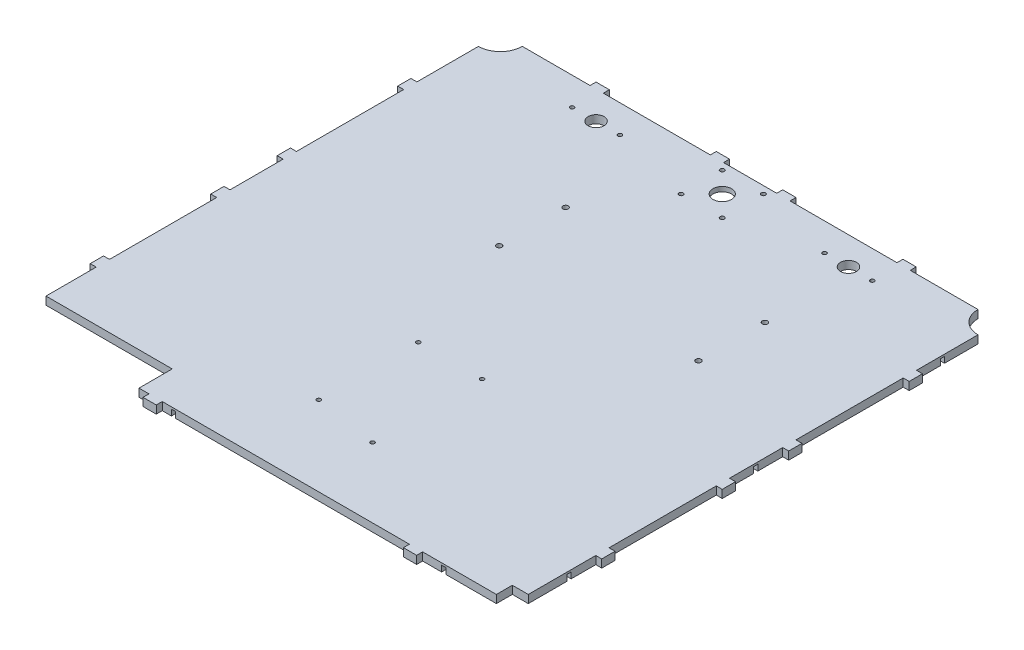
SolidWorks part; units mm, degrees
ref_plane "Alzado" through (0, 0, 0) normal (0, 0, 1) x (1, 0, 0)
ref_plane "Planta" through (0, 0, 0) normal (0, 1, 0) x (1, 0, 0)
ref_plane "Vista lateral" through (0, 0, 0) normal (1, 0, 0) x (0, 0, -1)
sketch "Croquis1" plane through (0, 0, 0) normal (0, 1, 0) x (1, 0, 0)
  line L0 (0, 0) -> (67.5, 0)
  line L1 (188, 367) -> (188, 375.2829) construction
  line L4 (77.5, 0) -> (102.5, 0)
  line L5 (0, 0) -> (0, 62.8)
  line L6 (0, 62.8) -> (-4.5, 62.8)
  line L7 (-4.5, 62.8) -> (-4.5, 72.8)
  line L8 (-4.5, 72.8) -> (0, 72.8)
  line L9 (0, 72.8) -> (0, 153.5)
  line L10 (0, 153.5) -> (-4.5, 153.5)
  line L11 (-4.5, 153.5) -> (-4.5, 163.5)
  line L12 (-4.5, 163.5) -> (0, 163.5)
  line L13 (0, 163.5) -> (0, 203.5)
  line L14 (0, 183.5) -> (180.5, 183.5) construction
  line L15 (188, 367) -> (188, 0) construction
  line L16 (-4.5, 203.5) -> (0, 203.5)
  line L17 (-4.5, 213.5) -> (-4.5, 203.5)
  line L18 (0, 213.5) -> (-4.5, 213.5)
  line L19 (0, 294.2) -> (0, 213.5)
  line L20 (-4.5, 294.2) -> (0, 294.2)
  line L21 (-4.5, 304.2) -> (-4.5, 294.2)
  line L22 (0, 304.2) -> (-4.5, 304.2)
  line L23 (0, 304.2) -> (0, 350.5)
  line L24 (16.5, 367) -> (67.5, 367)
  line L25 (67.5, 367) -> (67.5, 371.5)
  line L26 (67.5, 371.5) -> (77.5, 371.5)
  line L27 (77.5, 371.5) -> (77.5, 367)
  line L28 (77.5, 367) -> (158, 367)
  line L29 (158, 367) -> (158, 371.5)
  line L30 (158, 371.5) -> (168, 371.5)
  line L31 (168, 371.5) -> (168, 367)
  line L32 (168, 367) -> (208, 367)
  line L33 (376, 163.5) -> (376, 203.5)
  line L34 (380.5, 163.5) -> (376, 163.5)
  line L35 (380.5, 153.5) -> (380.5, 163.5)
  line L36 (376, 153.5) -> (380.5, 153.5)
  line L37 (376, 72.8) -> (376, 153.5)
  line L38 (380.5, 72.8) -> (376, 72.8)
  line L39 (380.5, 62.8) -> (380.5, 72.8)
  line L40 (376, 62.8) -> (380.5, 62.8)
  line L41 (376, 0) -> (376, 62.8)
  line L42 (298.5, -4.5) -> (298.5, 0)
  line L43 (308.5, -4.5) -> (298.5, -4.5)
  line L44 (308.5, 0) -> (308.5, -4.5)
  line L45 (376, 0) -> (308.5, 0)
  line L46 (208, 371.5) -> (208, 367)
  line L47 (218, 371.5) -> (208, 371.5)
  line L48 (218, 367) -> (218, 371.5)
  line L49 (298.5, 367) -> (218, 367)
  line L50 (298.5, 371.5) -> (298.5, 367)
  line L51 (308.5, 371.5) -> (298.5, 371.5)
  line L52 (308.5, 367) -> (308.5, 371.5)
  line L53 (359.5, 367) -> (308.5, 367)
  line L54 (376, 350.5) -> (376, 304.2)
  line L55 (376, 304.2) -> (380.5, 304.2)
  line L56 (380.5, 304.2) -> (380.5, 294.2)
  line L57 (380.5, 294.2) -> (376, 294.2)
  line L58 (376, 294.2) -> (376, 213.5)
  line L59 (376, 213.5) -> (380.5, 213.5)
  line L60 (380.5, 213.5) -> (380.5, 203.5)
  line L61 (380.5, 203.5) -> (376, 203.5)
  line L62 (102.5, 0) -> (102.5, 14.5062) construction
  line L63 (112.5, 0) -> (298.5, 0)
  line L64 (67.5, 0) -> (77.5, 0)
  line L65 (102.5, 0) -> (102.5, -4.5)
  line L66 (102.5, -4.5) -> (112.5, -4.5)
  line L67 (112.5, 0) -> (112.5, -4.5)
  arc A0 (0, 350.5) -> (16.5, 367) centre (0, 367) ccw
  arc A1 (376, 350.5) -> (359.5, 367) centre (376, 367) cw
  dimension "D8" = 33
  dimension "D14" = 46.3
  dimension "D2" = 20
  dimension "D5" = 62.8
  dimension "D6" = 4.5
  dimension "D7" = 10
  dimension "D9" = 10
  dimension "D10" = 20
  dimension "D11" = 51
  dimension "D12" = 10
  dimension "D13" = 4.5
  dimension "D15" = 10
  dimension "D16" = 16.5
  dimension "D17" = 16.5
  dimension "D18" = 25
  dimension "D19" = 10
extrude "Saliente-Extruir1" add sketch "Croquis1" against normal blind 6
sketch "Croquis3" plane through (0, -6, 0) normal (0, -1, 0) x (1, 0, 0)
  line L0 (324.3519, 0) -> (324.3519, -11.6932) construction
  line L1 (325.9019, -6.5002) -> (325.9019, 0)
  line L2 (327.1922, -8.0283) -> (327.1922, -9.5783)
  line L3 (322.2204, -10.8802) -> (322.3896, -10.8802)
  line L4 (325.9019, 0) -> (322.8019, 0)
  line L5 (321.5115, -8.0283) -> (321.5115, -9.5783)
  line L6 (326.4834, -10.8802) -> (326.3141, -10.8802)
  line L7 (322.8019, -6.5002) -> (322.8019, 0)
  line L8 (0, -323.9093) -> (6.5002, -323.9093) construction
  line L9 (324.3519, -11.6932) -> (324.3519, 0.5178) construction
  line L10 (188, 0) -> (188, -367) construction
  line L11 (324.3519, -367) -> (324.3519, -355.3068) construction
  line L12 (208, -367) -> (168, -367) construction
  line L13 (322.8019, -360.4998) -> (322.8019, -367)
  line L14 (8.0283, -326.7496) -> (9.5783, -326.7496)
  line L15 (10.8802, -321.7778) -> (10.8802, -321.947)
  line L16 (6.5002, -322.3593) -> (0, -322.3593)
  line L17 (6.5002, -325.4593) -> (0, -325.4593)
  line L18 (10.8802, -326.0408) -> (10.8802, -325.8715)
  line L19 (0, -323.9093) -> (11.6932, -323.9093) construction
  line L20 (321.5115, -358.9717) -> (321.5115, -357.4217)
  line L21 (0, -322.3593) -> (0, -325.4593)
  line L22 (0, -42.91) -> (11.6932, -42.91) construction
  line L23 (6.5002, -41.36) -> (0, -41.36)
  line L24 (10.8802, -45.0415) -> (10.8802, -44.8722)
  line L25 (8.0283, -40.0697) -> (9.5783, -40.0697)
  line L26 (0, -44.46) -> (0, -41.36)
  line L27 (10.8802, -40.7785) -> (10.8802, -40.9478)
  line L28 (8.0283, -45.7503) -> (9.5783, -45.7503)
  line L29 (6.5002, -44.46) -> (0, -44.46)
  line L30 (326.4834, -356.1198) -> (326.3141, -356.1198)
  line L31 (8.0283, -321.0689) -> (9.5783, -321.0689)
  line L32 (121.0007, 0) -> (121.0007, -11.6932) construction
  line L33 (0, -183.2411) -> (376, -183.2411) construction
  line L34 (322.8019, -367) -> (325.9019, -367)
  line L35 (327.1922, -358.9717) -> (327.1922, -357.4217)
  line L36 (8.0283, -186.246) -> (9.5783, -186.246)
  line L37 (10.8802, -181.2741) -> (10.8802, -181.4434)
  line L38 (6.5002, -181.8556) -> (0, -181.8556)
  line L39 (6.5002, -184.9556) -> (0, -184.9556)
  line L40 (10.8802, -185.5371) -> (10.8802, -185.3679)
  line L41 (0, -183.4056) -> (11.6932, -183.4056) construction
  line L42 (0, -181.8556) -> (0, -184.9556)
  line L43 (8.0283, -180.5653) -> (9.5783, -180.5653)
  line L44 (122.5507, -6.5002) -> (122.5507, 0)
  line L45 (123.841, -8.0283) -> (123.841, -9.5783)
  line L46 (118.8692, -10.8802) -> (119.0384, -10.8802)
  line L47 (122.5507, 0) -> (119.4507, 0)
  line L48 (118.1603, -8.0283) -> (118.1603, -9.5783)
  line L49 (123.1322, -10.8802) -> (122.9629, -10.8802)
  line L50 (376, -42.7364) -> (364.3068, -42.7364) construction
  line L51 (369.4998, -44.2864) -> (376, -44.2864)
  line L52 (367.9717, -45.5768) -> (366.4217, -45.5768)
  line L53 (365.1198, -40.6049) -> (365.1198, -40.7742)
  line L54 (376, -44.2864) -> (376, -41.1864)
  line L55 (367.9717, -39.8961) -> (366.4217, -39.8961)
  line L56 (365.1198, -44.8679) -> (365.1198, -44.6987)
  line L57 (369.4998, -41.1864) -> (376, -41.1864)
  line L58 (376, -183.2411) -> (364.3068, -183.2411) construction
  line L59 (367.9717, -180.4008) -> (366.4217, -180.4008)
  line L60 (376, -181.6911) -> (376, -184.7911)
  line L61 (365.1198, -185.3726) -> (365.1198, -185.2033)
  line L62 (369.4998, -184.7911) -> (376, -184.7911)
  line L63 (369.4998, -181.6911) -> (376, -181.6911)
  line L64 (365.1198, -181.1096) -> (365.1198, -181.2788)
  line L65 (367.9717, -186.0814) -> (366.4217, -186.0814)
  line L66 (376, -323.728) -> (364.3068, -323.728) construction
  line L67 (369.4998, -325.278) -> (376, -325.278)
  line L68 (365.1198, -321.5965) -> (365.1198, -321.7657)
  line L69 (367.9717, -326.5683) -> (366.4217, -326.5683)
  line L70 (376, -322.178) -> (376, -325.278)
  line L71 (365.1198, -325.8594) -> (365.1198, -325.6902)
  line L72 (367.9717, -320.8876) -> (366.4217, -320.8876)
  line L73 (369.4998, -322.178) -> (376, -322.178)
  line L74 (324.3519, -355.9508) -> (324.3519, -367) construction
  line L75 (51.6481, -367) -> (51.6481, -355.3068) construction
  line L76 (50.0981, -360.4998) -> (50.0981, -367)
  line L77 (48.8078, -358.9717) -> (48.8078, -357.4217)
  line L78 (53.7796, -356.1198) -> (53.6104, -356.1198)
  line L79 (50.0981, -367) -> (53.1981, -367)
  line L80 (54.4885, -358.9717) -> (54.4885, -357.4217)
  line L81 (51.6481, -355.9508) -> (51.6481, -367) construction
  line L82 (51.6481, 0.5178) -> (51.6481, -24.8622) construction
  line L83 (322.2204, -356.1198) -> (322.3896, -356.1198)
  line L84 (119.4507, -6.5002) -> (119.4507, 0)
  line L85 (121.0007, -11.6932) -> (121.0007, 0) construction
  line L86 (325.9019, -360.4998) -> (325.9019, -367)
  line L87 (324.3519, -355.3068) -> (324.3519, -367.5178) construction
  line L88 (49.5166, -356.1198) -> (49.6859, -356.1198)
  line L89 (53.1981, -360.4998) -> (53.1981, -367)
  line L90 (51.6481, -355.3068) -> (51.6481, -367.5178) construction
  line L96 (51.6481, -355.9508) -> (51.6481, -367) construction
  arc A0 (327.1922, -8.0283) -> (325.9019, -6.5002) centre (325.6422, -8.0283) ccw
  arc A1 (322.3896, -10.8802) -> (326.3141, -10.8802) centre (324.3519, -8.9187) ccw
  arc A2 (322.2204, -10.8802) -> (321.5115, -9.5783) centre (323.0615, -9.5783) cw
  arc A3 (326.4834, -10.8802) -> (327.1922, -9.5783) centre (325.6422, -9.5783) ccw
  arc A4 (321.5115, -8.0283) -> (322.8019, -6.5002) centre (323.0615, -8.0283) cw
  arc A5 (8.0283, -321.0689) -> (6.5002, -322.3593) centre (8.0283, -322.6189) ccw
  arc A6 (8.0283, -326.7496) -> (6.5002, -325.4593) centre (8.0283, -325.1996) cw
  arc A7 (10.8802, -326.0408) -> (9.5783, -326.7496) centre (9.5783, -325.1996) cw
  arc A8 (10.8802, -321.7778) -> (9.5783, -321.0689) centre (9.5783, -322.6189) ccw
  arc A9 (10.8802, -325.8715) -> (10.8802, -321.947) centre (8.9187, -323.9093) ccw
  arc A10 (8.0283, -40.0697) -> (6.5002, -41.36) centre (8.0283, -41.6197) ccw
  arc A11 (10.8802, -45.0415) -> (9.5783, -45.7503) centre (9.5783, -44.2003) cw
  arc A12 (10.8802, -40.7785) -> (9.5783, -40.0697) centre (9.5783, -41.6197) ccw
  arc A13 (10.8802, -40.9478) -> (10.8802, -44.8722) centre (8.9187, -42.91) cw
  arc A14 (8.0283, -45.7503) -> (6.5002, -44.46) centre (8.0283, -44.2003) cw
  arc A15 (8.0283, -180.5653) -> (6.5002, -181.8556) centre (8.0283, -182.1153) ccw
  arc A16 (8.0283, -186.246) -> (6.5002, -184.9556) centre (8.0283, -184.696) cw
  arc A17 (10.8802, -185.5371) -> (9.5783, -186.246) centre (9.5783, -184.696) cw
  arc A18 (10.8802, -181.2741) -> (9.5783, -180.5653) centre (9.5783, -182.1153) ccw
  arc A19 (10.8802, -185.3679) -> (10.8802, -181.4434) centre (8.9187, -183.4056) ccw
  arc A20 (123.841, -8.0283) -> (122.5507, -6.5002) centre (122.291, -8.0283) ccw
  arc A21 (119.0384, -10.8802) -> (122.9629, -10.8802) centre (121.0007, -8.9187) ccw
  arc A22 (118.8692, -10.8802) -> (118.1603, -9.5783) centre (119.7103, -9.5783) cw
  arc A23 (123.1322, -10.8802) -> (123.841, -9.5783) centre (122.291, -9.5783) ccw
  arc A24 (118.1603, -8.0283) -> (119.4507, -6.5002) centre (119.7103, -8.0283) cw
  arc A25 (367.9717, -45.5768) -> (369.4998, -44.2864) centre (367.9717, -44.0268) ccw
  arc A26 (365.1198, -40.7742) -> (365.1198, -44.6987) centre (367.0813, -42.7364) ccw
  arc A27 (365.1198, -40.6049) -> (366.4217, -39.8961) centre (366.4217, -41.4461) cw
  arc A28 (365.1198, -44.8679) -> (366.4217, -45.5768) centre (366.4217, -44.0268) ccw
  arc A29 (367.9717, -39.8961) -> (369.4998, -41.1864) centre (367.9717, -41.4461) cw
  arc A30 (365.1198, -185.2033) -> (365.1198, -181.2788) centre (367.0813, -183.2411) cw
  arc A31 (365.1198, -181.1096) -> (366.4217, -180.4008) centre (366.4217, -181.9508) cw
  arc A32 (365.1198, -185.3726) -> (366.4217, -186.0814) centre (366.4217, -184.5314) ccw
  arc A33 (367.9717, -186.0814) -> (369.4998, -184.7911) centre (367.9717, -184.5314) ccw
  arc A34 (367.9717, -180.4008) -> (369.4998, -181.6911) centre (367.9717, -181.9508) cw
  arc A35 (367.9717, -326.5683) -> (369.4998, -325.278) centre (367.9717, -325.0183) ccw
  arc A36 (365.1198, -321.5965) -> (366.4217, -320.8876) centre (366.4217, -322.4376) cw
  arc A37 (365.1198, -325.8594) -> (366.4217, -326.5683) centre (366.4217, -325.0183) ccw
  arc A38 (365.1198, -325.6902) -> (365.1198, -321.7657) centre (367.0813, -323.728) cw
  arc A39 (367.9717, -320.8876) -> (369.4998, -322.178) centre (367.9717, -322.4376) cw
  arc A40 (48.8078, -358.9717) -> (50.0981, -360.4998) centre (50.3578, -358.9717) ccw
  arc A41 (53.6104, -356.1198) -> (49.6859, -356.1198) centre (51.6481, -358.0813) ccw
  arc A42 (53.7796, -356.1198) -> (54.4885, -357.4217) centre (52.9385, -357.4217) cw
  arc A43 (49.5166, -356.1198) -> (48.8078, -357.4217) centre (50.3578, -357.4217) ccw
  arc A44 (54.4885, -358.9717) -> (53.1981, -360.4998) centre (52.9385, -358.9717) cw
  arc A50 (321.5115, -358.9717) -> (322.8019, -360.4998) centre (323.0615, -358.9717) ccw
  arc A51 (326.3141, -356.1198) -> (322.3896, -356.1198) centre (324.3519, -358.0813) ccw
  arc A52 (326.4834, -356.1198) -> (327.1922, -357.4217) centre (325.6422, -357.4217) cw
  arc A53 (322.2204, -356.1198) -> (321.5115, -357.4217) centre (323.0615, -357.4217) ccw
  arc A54 (327.1922, -358.9717) -> (325.9019, -360.4998) centre (325.6422, -358.9717) cw
  dimension "D4" = 1.55
  dimension "D6" = 0.4122
  dimension "D8" = 1.5281
  dimension "D10" = 0.1692
  dimension "D23" = 6.5002
  dimension "D25" = 1.55
  dimension "D24" = 1.55
  dimension "D31" = 1.55
  dimension "D33" = 11.6932
  dimension "D26" = 1.55
  dimension "D5" = 1.55
  dimension "D1" = 6.5002
  dimension "D7" = 1.55
  dimension "D9" = 1.55
  dimension "D11" = 11.6932
  dimension "D27" = 4.38
  dimension "D28" = 0.4122
  dimension "D29" = 1.55
  dimension "D30" = 1.5281
  dimension "D32" = 0.1692
  dimension "D34" = 51.6481
extrude "Cortar-Extruir1" cut sketch "Croquis3" against normal blind 4.5
sketch "Croquis5" plane through (0, 0, 0) normal (0, 1, 0) x (1, 0, 0)
  line L0 (188, 367) -> (188, 346) construction
  line L1 (0, 0) -> (12, 0)
  line L2 (0, 0) -> (0, 12)
  line L3 (0, 12) -> (12, 12)
  line L4 (12, 0) -> (12, 12)
  line L5 (376, 0) -> (364, 0)
  line L6 (376, 0) -> (376, 12)
  line L7 (376, 12) -> (364, 12)
  line L8 (364, 0) -> (364, 12)
  line L9 (158, 367) -> (77.5, 367) construction
  line L10 (67.5, 367) -> (16.5, 367) construction
  line L11 (208, 367) -> (168, 367) construction
  line L12 (172.5, 361.5) -> (172.5, 346) construction
  line L13 (172.5, 346) -> (188, 346) construction
  line L14 (188, 346) -> (73.5, 346) construction
  circle A0 centre (188, 346) radius 7
  circle A1 centre (172.5, 361.5) radius 1.6
  circle A2 centre (203.5, 361.5) radius 1.6
  circle A3 centre (203.5, 330.5) radius 1.6
  circle A4 centre (172.5, 330.5) radius 1.6
  circle A5 centre (93, 346) radius 6
  circle A6 centre (111, 346) radius 1.5
  circle A7 centre (75, 346) radius 1.5
  circle A8 centre (301, 346) radius 1.5
  circle A9 centre (265, 346) radius 1.5
  circle A10 centre (283, 346) radius 6
  dimension "D4" = 14
  dimension "D5" = 3.2
  dimension "D9" = 3
  dimension "D8" = 12
  dimension "D11" = 3
  dimension "D1" = 12
  dimension "D2" = 12
  dimension "D3" = 21
  dimension "D6" = 15.5
  dimension "D7" = 15.5
  dimension "D10" = 18
  dimension "D12" = 18
  dimension "D13" = 95
  dimension "D16" = 21
  dimension "D17" = 21
extrude "Cortar-Extruir2" cut sketch "Croquis5" against normal up to surface (6 mm away) up to face at (193.3419, -6, -193.3919)
sketch "Croquis7" plane through (0, 0, 0) normal (0, 1, 0) x (1, 0, 0)
  line L1 (12, 0) -> (102.5, 0) construction
  line L3 (95, 0) -> (0, 0)
  line L4 (95, 0) -> (95, 25)
  line L5 (95, 25) -> (0, 25)
  line L6 (0, 0) -> (0, 25)
  line L7 (0, 62.8) -> (0, 12) construction
  circle A0 centre (137.7441, 278.3503) radius 2
  circle A1 centre (137.7441, 228.3503) radius 2
  circle A2 centre (287.7441, 228.3503) radius 2
  circle A3 centre (287.7441, 278.3503) radius 2
  circle A4 centre (218.2736, 134.9894) radius 1.5
  circle A5 centre (170.2736, 134.9894) radius 1.5
  circle A6 centre (218.2736, 52.4894) radius 1.5
  circle A7 centre (170.2736, 59.9894) radius 1.5
  dimension "D5" = 4
  dimension "D6" = 4
  dimension "D7" = 4
  dimension "D8" = 4
  dimension "D1" = 3
  dimension "D4" = 3
  dimension "D10" = 3
  dimension "D12" = 3
  dimension "D2" = 50
  dimension "D3" = 50
  dimension "D9" = 48
  dimension "D11" = 82.5
  dimension "D13" = 75
  dimension "D14" = 95
  dimension "D15" = 25
  dimension "D16" = 150
extrude "Cortar-Extruir4" cut sketch "Croquis7" against normal blind 10
sketch "Croquis8" plane through (0, -6, 0) normal (0, -1, 0) x (1, 0, 0)
  circle A2 centre (265, -346) radius 1.5 construction
  circle A4 centre (188, -346) radius 7 construction
  circle A5 centre (188, -346) radius 7
  circle A6 centre (265, -346) radius 1.5
  circle A7 centre (188, -346) radius 11
  circle A8 centre (111, -346) radius 4.5
  circle A9 centre (75, -346) radius 4.5
  circle A10 centre (265, -346) radius 4.5
  circle A11 centre (301, -346) radius 4.5
  dimension "D1" = 95
  dimension "D2" = 95
extrude "Cortar-Extruir5" cut sketch "Croquis8" against normal blind 2.5
equation "\"Ancho_panel\"= 385'Ancho del panel"
equation "\"Alto_panel\"= 420'Alto del panel izquierdo"
equation "\"Altura_base_taladros\"= 70'Alto taladros de la base eje Z"
equation "\"Altura_superior_taladros\"= 8mm'Distancia taladros a top"
equation "\"Distancia_vert_entre_horizontales_ensambles\"= \"Alto_panel\" - \"Altura_base_taladros\" - \"Altura_superior_taladros\"'Distancia vertical entre horizontales de ensambles"
equation "\"Latrales_separacion_barras_a_escalon_bajo\"= 12.5'Separación entre las barras y el escalón inferior de la parte superior"
equation "\"Espacio_tensor_correa_motor\"= 8.5mm'Espacio para mover el motor en vertical y tensar la correa"
equation "\"Ancho_panel_interior\"= \"Ancho_panel\" - 9mm'Ancho panel interior"
equation "\"Fondo_panel_interior\"= \"Ancho_panel\" - 9mm'Fondo panel interior"
